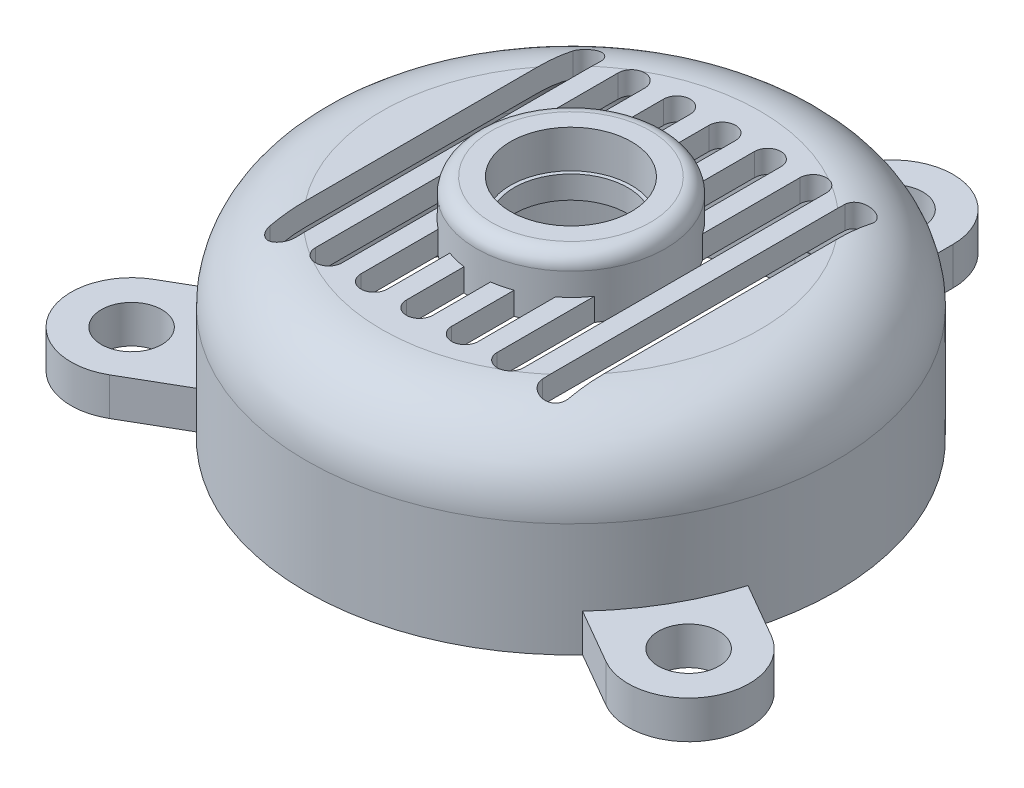
SolidWorks part; units mm, degrees
ref_plane "Front Plane" through (0, 0, 0) normal (0, 0, 1) x (1, 0, 0)
ref_plane "Top Plane" through (0, 0, 0) normal (0, 1, 0) x (1, 0, 0)
ref_plane "Right Plane" through (0, 0, 0) normal (1, 0, 0) x (0, 0, -1)
sketch "Sketch2" plane through (0, 0, 0) normal (0, 1, 0) x (1, 0, 0)
  circle A0 centre (0, 0) radius 35
  dimension "D1" = 70
extrude "Boss-Extrude1" add sketch "Sketch2" along normal blind 25
fillet "Fillet1" radius 10 1 edges at (0, 25, 35)
sketch "Sketch3" plane through (0, 0, 0) normal (0, 1, 0) x (1, 0, 0)
  line L0 (0, 0) -> (0, 42.5) construction
  line L1 (0, 42.5) -> (0, 31.9181) construction
  line L2 (8, 42.5) -> (8, 31.9181)
  line L3 (-8, 42.5) -> (-8, 31.9181)
  line L4 (-8, 31.9181) -> (8, 31.9181)
  line L5 (32.8061, -28.1782) -> (23.6419, -22.8873)
  line L6 (40.8061, -14.3218) -> (31.6419, -9.0309)
  line L7 (31.6419, -9.0309) -> (23.6419, -22.8873)
  line L8 (-40.8061, -14.3218) -> (-31.6419, -9.0309)
  line L9 (-32.8061, -28.1782) -> (-23.6419, -22.8873)
  line L10 (-23.6419, -22.8873) -> (-31.6419, -9.0309)
  circle A0 centre (0, 42.5) radius 4
  arc A1 (8, 42.5) -> (-8, 42.5) centre (0, 42.5) ccw
  circle A3 centre (36.8061, -21.25) radius 4
  arc A4 (32.8061, -28.1782) -> (40.8061, -14.3218) centre (36.8061, -21.25) ccw
  circle A5 centre (-36.8061, -21.25) radius 4
  arc A6 (-40.8061, -14.3218) -> (-32.8061, -28.1782) centre (-36.8061, -21.25) ccw
  point P4 (0, 37.2091)
  point P25 (0, 0)
  dimension "D2" = 8
  dimension "D3" = 8
  dimension "D1" = 42.5
  dimension "D4" = 31.9181
  dimension "D5" = 3
shell "Shell2" thickness 3
extrude "Boss-Extrude2" add sketch "Sketch3" along normal blind 5
ref_plane "Plane1" through (0, 25, 0) normal (0, 1, 0) x (1, 0, 0)
sketch "Sketch6" plane through (0, 25, 0) normal (0, 1, 0) x (1, 0, 0)
  circle A0 centre (0, 0) radius 7.5
  circle A1 centre (0, 0) radius 12.5
  dimension "D1" = 15
  dimension "D2" = 25
extrude "Boss-Extrude3" add sketch "Sketch6" along normal blind 5
fillet "Fillet2" radius 2 1 edges at (0, 30, 12.5)
sketch "Sketch11" plane through (0, 25, 0) normal (0, 1, 0) x (1, 0, 0)
  circle A0 centre (0, 0) radius 8
  circle A1 centre (0, 0) radius 7.5 construction
  dimension "D1" = 16
extrude "Cut-Extrude1" cut sketch "Sketch11" against normal through all both and the other way through all
sketch "Sketch18" plane through (0, 25, 0) normal (0, 1, 0) x (1, 0, 0)
  line L0 (0, -20) -> (0, 20) construction
  line L1 (-1.75, -20) -> (-1.75, 20)
  line L2 (1.75, -20) -> (1.75, 20)
  line L3 (0, 0) -> (-1.75, 0) construction
  line L4 (6, -20) -> (6, 20) construction
  line L5 (4.25, -20) -> (4.25, 20)
  line L6 (7.75, -20) -> (7.75, 20)
  line L7 (12, -20) -> (12, 20) construction
  line L8 (10.25, -20) -> (10.25, 20)
  line L9 (13.75, -20) -> (13.75, 20)
  line L10 (18, -20) -> (18, 20) construction
  line L11 (16.25, -20) -> (16.25, 20)
  line L12 (19.75, -20) -> (19.75, 20)
  line L13 (-6, -20) -> (-6, 20) construction
  line L14 (-7.75, -20) -> (-7.75, 20)
  line L15 (-4.25, -20) -> (-4.25, 20)
  line L16 (-12, -20) -> (-12, 20) construction
  line L17 (-13.75, -20) -> (-13.75, 20)
  line L18 (-10.25, -20) -> (-10.25, 20)
  line L19 (-18, -20) -> (-18, 20) construction
  line L20 (-19.75, -20) -> (-19.75, 20)
  line L21 (-16.25, -20) -> (-16.25, 20)
  arc A0 (-1.75, -20) -> (1.75, -20) centre (0, -20) ccw
  arc A1 (1.75, 20) -> (-1.75, 20) centre (0, 20) ccw
  circle A2 centre (0, 0) radius 12.5 construction
  arc A3 (4.25, -20) -> (7.75, -20) centre (6, -20) ccw
  arc A4 (7.75, 20) -> (4.25, 20) centre (6, 20) ccw
  arc A5 (10.25, -20) -> (13.75, -20) centre (12, -20) ccw
  arc A6 (13.75, 20) -> (10.25, 20) centre (12, 20) ccw
  arc A7 (16.25, -20) -> (19.75, -20) centre (18, -20) ccw
  arc A8 (19.75, 20) -> (16.25, 20) centre (18, 20) ccw
  arc A9 (-7.75, -20) -> (-4.25, -20) centre (-6, -20) ccw
  arc A10 (-4.25, 20) -> (-7.75, 20) centre (-6, 20) ccw
  arc A11 (-13.75, -20) -> (-10.25, -20) centre (-12, -20) ccw
  arc A12 (-10.25, 20) -> (-13.75, 20) centre (-12, 20) ccw
  arc A13 (-19.75, -20) -> (-16.25, -20) centre (-18, -20) ccw
  arc A14 (-16.25, 20) -> (-19.75, 20) centre (-18, 20) ccw
  point P2 (0, 0)
  point P16 (6, 0)
  point P23 (12, 0)
  point P30 (18, 0)
  point P37 (-6, 0)
  point P44 (-12, 0)
  point P51 (-18, 0)
  dimension "D1" = 1.75
  dimension "D2" = 20
  dimension "D3" = 4
  dimension "D5" = 6
  dimension "D6" = 6
  dimension "D4" = 4
extrude "Cut-Extrude3" cut sketch "Sketch18" against normal through all
sketch "Sketch20" plane through (0, 25, 0) normal (0, 1, 0) x (1, 0, 0)
  circle A0 centre (0, 0) radius 7.5
  circle A1 centre (0, 0) radius 12.5
  dimension "D1" = 15
  dimension "D2" = 25
extrude "Boss-Extrude4" add sketch "Sketch20" against normal blind 3
